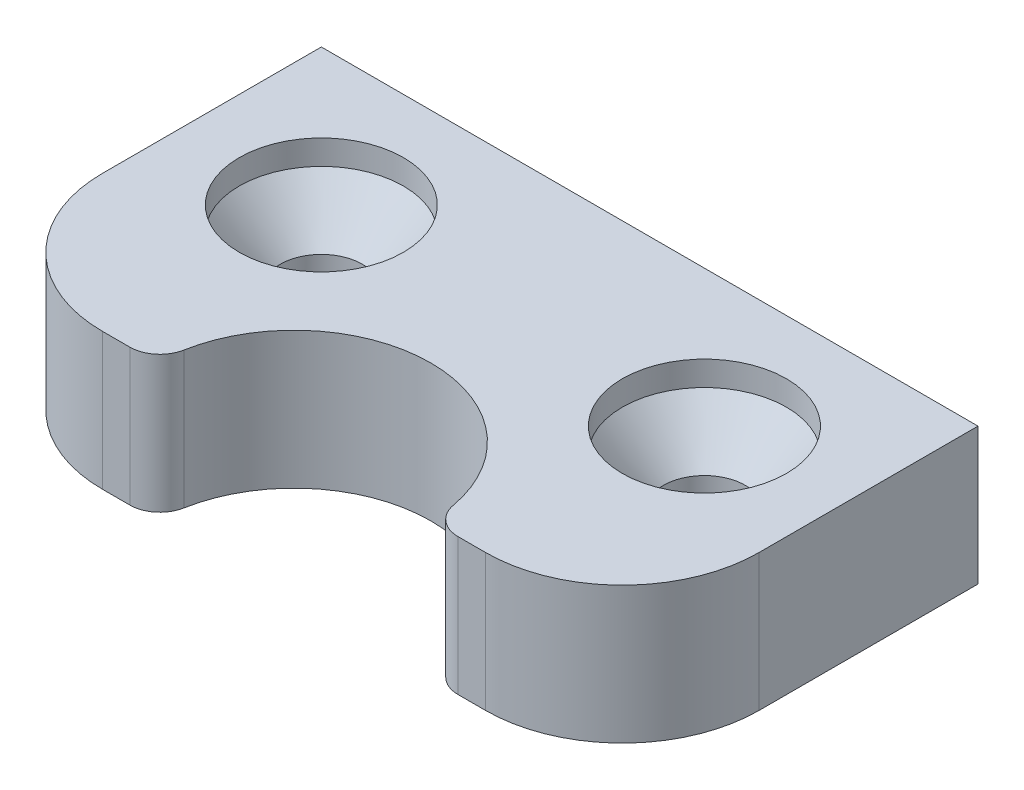
SolidWorks part; units mm, degrees
material "PVC 0.007 Plasticized"
ref_plane "Front Plane" through (0, 0, 0) normal (0, 0, 1) x (1, 0, 0)
ref_plane "Top Plane" through (0, 0, 0) normal (0, 1, 0) x (1, 0, 0)
ref_plane "Right Plane" through (0, 0, 0) normal (1, 0, 0) x (0, 0, -1)
other "Configuration Table"
sketch "Sketch1" plane through (0, 0, 0) normal (0, 1, 0) x (1, 0, 0)
  line L1 (0, 0) -> (30.48, 0)
  line L2 (0, 0) -> (0, 16.51)
  line L3 (0, 16.51) -> (30.48, 16.51)
  line L4 (30.48, 0) -> (30.48, 16.51)
  dimension "D1" = 30.48
  dimension "D2" = 16.51
extrude "Boss-Extrude1" add sketch "Sketch1" along normal blind 6.35
fillet "Fillet1" radius 6.35 2 edges at (0, 3.175, 0) (30.48, 3.175, 0)
sketch "Sketch2" plane through (0, 6.35, 0) normal (0, 1, 0) x (1, 0, 0)
  line L0 (6.35, 0) -> (24.13, 0) construction
  circle A0 centre (15.24, 0) radius 6.35
  dimension "D1" = 12.7
extrude "Cut-Extrude1" cut sketch "Sketch2" against normal blind 12.7
fillet "Fillet2" radius 1.397 2 edges at (21.59, 3.175, 0) (8.89, 3.175, 0)
sketch "Sketch3" plane through (0, 6.35, 0) normal (0, 1, 0) x (1, 0, 0)
  line L0 (0, 16.51) -> (0, 6.35) construction
  line L1 (30.48, 6.35) -> (30.48, 16.51) construction
  line L2 (30.48, 16.51) -> (0, 16.51) construction
  circle A0 centre (6.35, 10.16) radius 3.81
  circle A1 centre (24.13, 10.16) radius 3.81
  dimension "D5" = 7.62
  dimension "D6" = 7.62
  dimension "D1" = 6.35
  dimension "D2" = 6.35
  dimension "D3" = 6.35
  dimension "D4" = 6.35
extrude "Cut-Extrude2" cut sketch "Sketch3" against normal blind 1.143
hole_wizard "CSK for #0 Flat Head Socket Cap Screw1" positions "Sketch4" profile "Sketch5" countersink size "#0" standard "ANSI Inch" end condition through all
sketch "Sketch4" plane through (0, 5.207, 0) normal (0, 1, 0) x (1, 0, 0)
  point P0 (6.35, 10.16)
  point P3 (24.13, 10.16)
sketch "Sketch5" plane through (6.35, 5.207, -10.16) normal (1, 0, 0) x (0, 0, 1)
  line L0 (0, 0) -> (0, 5.207)
  line L1 (0, 5.207) -> (1.905, 5.207)
  line L2 (1.905, 5.207) -> (1.905, 2.1915)
  line L3 (1.905, 2.1915) -> (3.81, 0)
  line L5 (3.81, 0) -> (0, 0)
  line L6 (-1.905, 2.1915) -> (-3.81, 0) construction
  line L11 (0, -6.35) -> (0, 107.95) construction
  dimension "Thru Hole Dia." = 3.81
  dimension "Thru Hole Depth" = 5.207
  dimension "Near C'Sink Dia." = 7.62
  dimension "Near C'Sink Angle" = 82
sketch "Sketch6" plane through (0, 0, 0) normal (0, -1, 0) x (1, 0, 0)
  line L0 (15.24, -6.35) -> (15.24, -16.51) construction
  line L1 (30.48, -16.51) -> (0, -16.51) construction
  line L2 (6.35, -10.16) -> (24.13, -10.16) construction
  arc A0 (8.9941, -1.1451) -> (21.4859, -1.1451) centre (15.24, 0) ccw construction
  circle A1 centre (15.24, -10.16) radius 2.54
  dimension "D1" = 5.08
extrude "Cut-Extrude3" cut sketch "Sketch6" against normal blind 5.08
